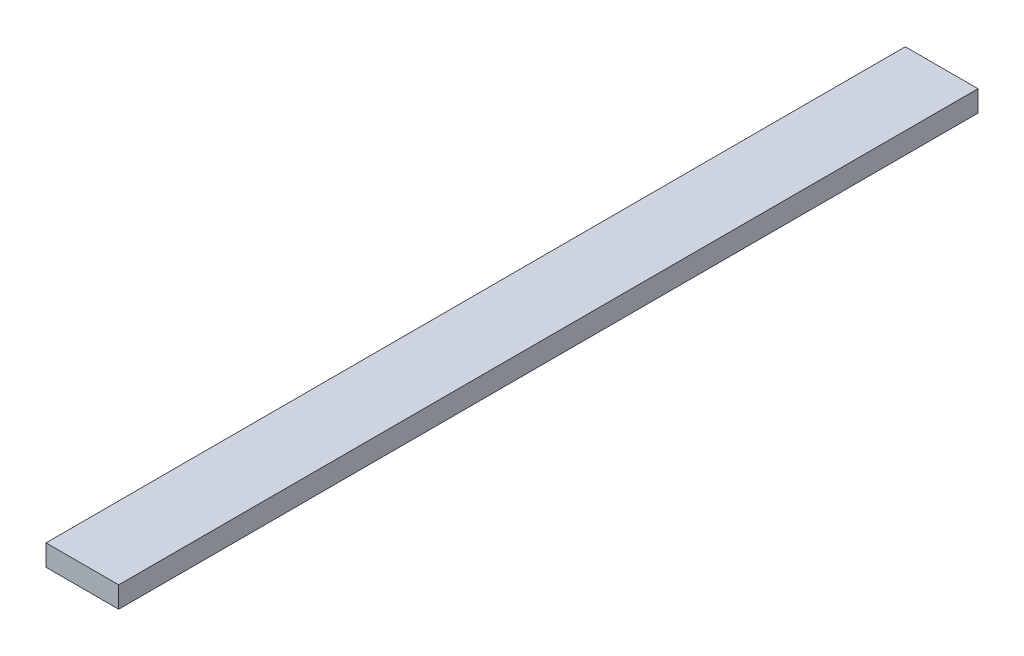
SolidWorks part; units mm, degrees
ref_plane "Front Plane" through (0, 0, 0) normal (0, 0, 1) x (1, 0, 0)
ref_plane "Top Plane" through (0, 0, 0) normal (0, 1, 0) x (1, 0, 0)
ref_plane "Right Plane" through (0, 0, 0) normal (1, 0, 0) x (0, 0, -1)
sketch "Sketch1" plane through (0, 0, 0) normal (0, 1, 0) x (1, 0, 0)
  line L1 (-6.1442, 145.3092) -> (7.8258, 145.3092)
  line L2 (-6.1442, 145.3092) -> (-6.1442, -19.7908)
  line L3 (-6.1442, -19.7908) -> (7.8258, -19.7908)
  line L4 (7.8258, 145.3092) -> (7.8258, -19.7908)
  dimension "D1" = 13.97
  dimension "D2" = 165.1
extrude "Boss-Extrude1" add sketch "Sketch1" along normal blind 4.064
